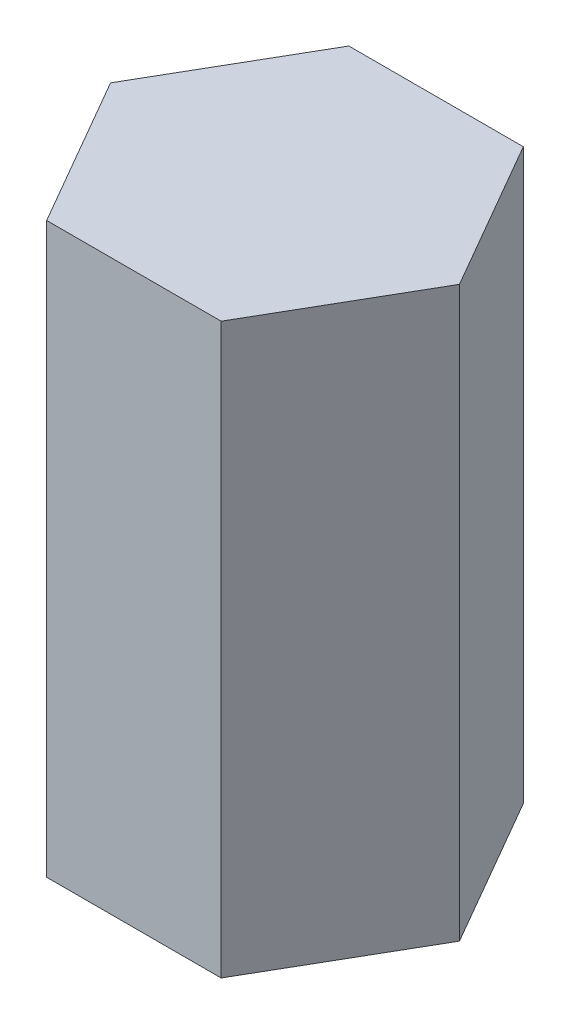
SolidWorks part; units mm, degrees
ref_plane "Front Plane" through (0, 0, 0) normal (0, 0, 1) x (1, 0, 0)
ref_plane "Top Plane" through (0, 0, 0) normal (0, 1, 0) x (1, 0, 0)
ref_plane "Right Plane" through (0, 0, 0) normal (1, 0, 0) x (0, 0, -1)
sketch "Sketch1" plane through (0, 0, 0) normal (0, 1, 0) x (1, 0, 0)
  line L1 (9.815, 0) -> (4.9075, 8.5)
  line L2 (4.9075, 8.5) -> (-4.9075, 8.5)
  line L3 (-4.9075, 8.5) -> (-9.815, 0)
  line L4 (-9.815, 0) -> (-4.9075, -8.5)
  line L5 (-4.9075, -8.5) -> (4.9075, -8.5)
  line L6 (4.9075, -8.5) -> (9.815, 0)
  circle A0 centre (0, 0) radius 8.5 construction
  dimension "D1" = 17
extrude "Boss-Extrude1" add sketch "Sketch1" along normal blind 32
